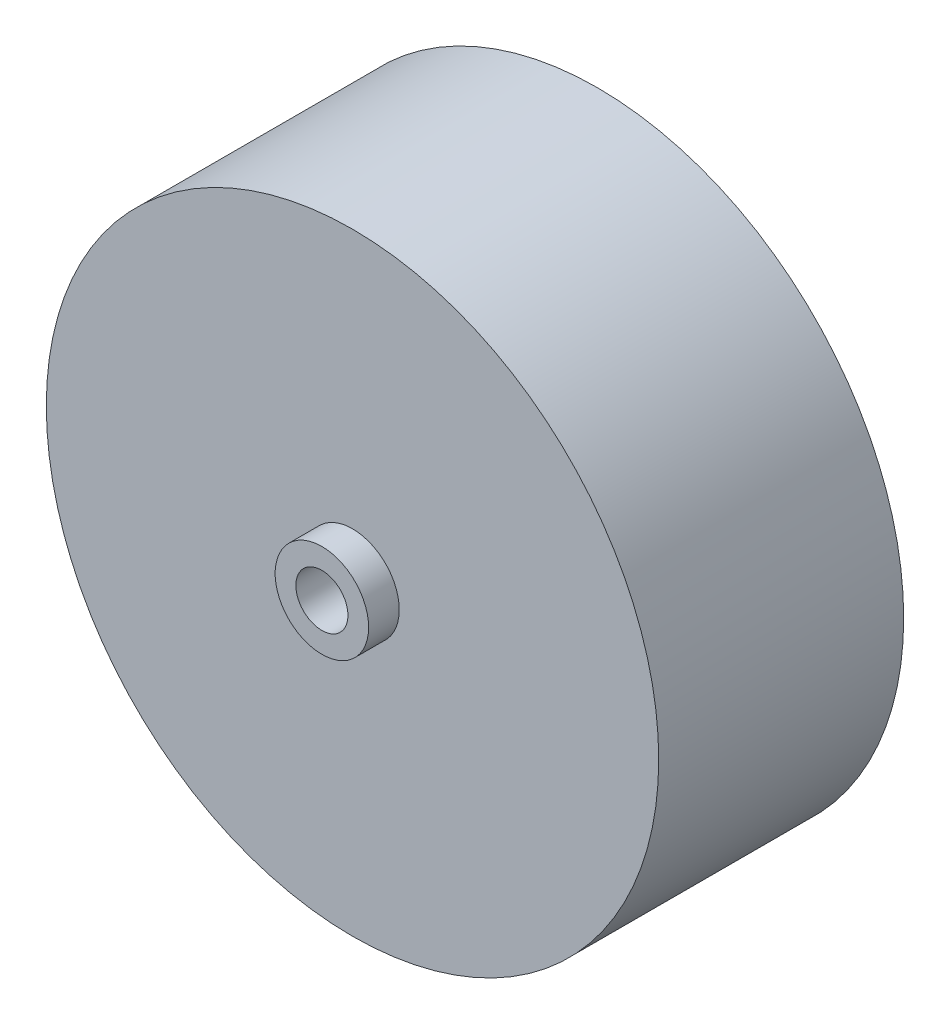
SolidWorks part; units mm, degrees
ref_plane "Front Plane" through (0, 0, 0) normal (0, 0, 1) x (1, 0, 0)
ref_plane "Top Plane" through (0, 0, 0) normal (0, 1, 0) x (1, 0, 0)
ref_plane "Right Plane" through (0, 0, 0) normal (1, 0, 0) x (0, 0, -1)
sketch "Sketch1" plane through (0, 0, 0) normal (0, 0, 1) x (1, 0, 0)
  circle A0 centre (0, 0) radius 31.75
extrude "Boss-Extrude1" add sketch "Sketch1" along normal blind 25.4
sketch "Sketch2" plane through (0, 0, 25.4) normal (0, 0, 1) x (1, 0, 0)
  circle A0 centre (0, 0) radius 2.7
  circle A1 centre (0, 0) radius 4.8456
extrude "Boss-Extrude2" add sketch "Sketch2" along normal blind 3.175
sketch "Sketch3" plane through (0, 0, 25.4) normal (0, 0, 1) x (1, 0, 0)
  circle A0 centre (0, 0) radius 2.7
extrude "Cut-Extrude1" cut sketch "Sketch3" against normal up to next
